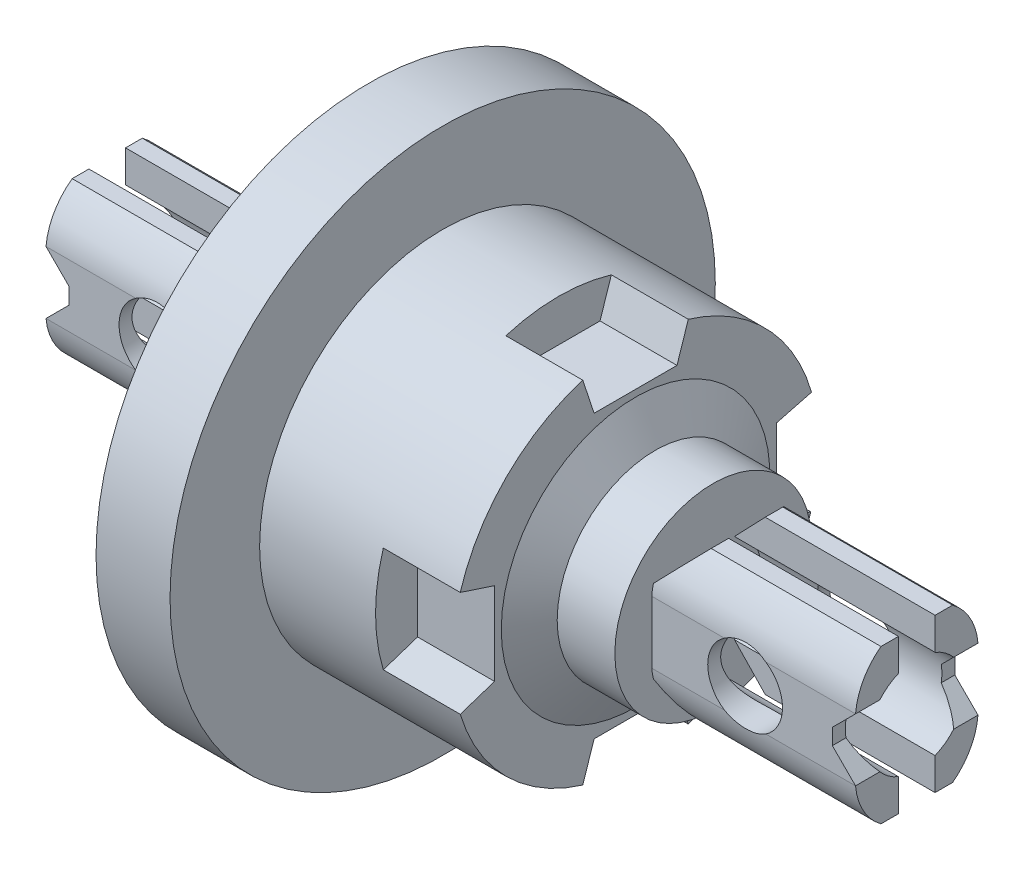
SolidWorks part; units mm, degrees
ref_plane "Front Plane" through (0, 0, 0) normal (0, 0, 1) x (1, 0, 0)
ref_plane "Top Plane" through (0, 0, 0) normal (0, 1, 0) x (1, 0, 0)
ref_plane "Right Plane" through (0, 0, 0) normal (1, 0, 0) x (0, 0, -1)
sketch "Sketch1" plane through (0, 0, 0) normal (0, 0, 1) x (1, 0, 0)
  line L0 (-42.2453, 0) -> (55.943, 0) construction
  line L1 (32.766, 0) -> (32.766, 8.001) construction
  line L2 (32.766, 8.001) -> (28.067, 8.001) construction
  line L3 (28.067, 8.001) -> (26.4541, 10.9474) construction
  line L4 (26.4541, 10.9474) -> (26.4541, 14.9225) construction
  line L5 (26.4541, 14.9225) -> (10.7315, 14.9225) construction
  line L6 (10.7315, 14.9225) -> (10.7315, 22.225) construction
  line L7 (10.7315, 22.225) -> (4.699, 22.225) construction
  line L8 (4.699, 22.225) -> (4.699, 8.001) construction
  line L9 (4.699, 8.001) -> (0, 8.001) construction
  line L10 (0, 8.001) -> (0, 0) construction
  line L11 (32.766, 0) -> (32.766, 8.001)
  line L12 (32.766, 8.001) -> (28.067, 8.001)
  line L13 (28.067, 8.001) -> (26.4541, 10.9474)
  line L14 (26.4541, 10.9474) -> (26.4541, 14.9225)
  line L15 (26.4541, 14.9225) -> (10.7315, 14.9225)
  line L16 (10.7315, 14.9225) -> (10.7315, 22.225)
  line L17 (10.7315, 22.225) -> (4.699, 22.225)
  line L18 (4.699, 22.225) -> (4.699, 8.001)
  line L19 (4.699, 8.001) -> (0, 8.001)
  line L20 (0, 8.001) -> (0, 0)
  line L21 (32.766, 0) -> (0, 0)
  dimension "D1" = 8.001
  dimension "D2" = 14.9225
  dimension "D3" = 22.225
  dimension "D4" = 4.699
  dimension "D5" = 15.7226
  dimension "D6" = 6.0325
  dimension "D7" = 4.699
  dimension "D8" = 32.766
  dimension "D9" = 2.9464
revolve "Revolve1" add sketch "Sketch1" angle 360 about L0
sketch "Sketch2" plane through (26.4541, 0, 0) normal (1, 0, 0) x (0, 0, -1)
  line L0 (0, 14.9225) -> (0, 11.4935) construction
  line L1 (-11.4935, -3.3782) -> (-11.4935, 3.3782)
  line L2 (-3.3782, -11.4935) -> (3.3782, -11.4935)
  line L3 (14.9225, 0) -> (11.4935, 0) construction
  line L4 (0, -14.9225) -> (0, -11.4935) construction
  line L5 (-14.9225, 0) -> (-11.4935, 0) construction
  line L6 (11.4935, 3.3782) -> (11.4935, -3.3782)
  line L7 (3.3782, 11.4935) -> (-3.3782, 11.4935)
  line L8 (3.3782, 11.4935) -> (4.3001, 14.2895)
  line L9 (-3.3782, 11.4935) -> (-4.3001, 14.2895)
  line L10 (-11.4935, 3.3782) -> (-14.2895, 4.3001)
  line L11 (-11.4935, -3.3782) -> (-14.2895, -4.3001)
  line L12 (3.3782, -11.4935) -> (4.3001, -14.2895)
  line L13 (-3.3782, -11.4935) -> (-4.3001, -14.2895)
  line L14 (11.4935, -3.3782) -> (14.2895, -4.3001)
  line L15 (11.4935, 3.3782) -> (14.3437, 4.1158)
  circle A0 centre (0, 0) radius 14.9225 construction
  circle A1 centre (0, 0) radius 14.9225 construction
  arc A2 (-14.2895, -4.3001) -> (-14.2895, 4.3001) centre (0, 0) cw
  arc A3 (-4.3001, -14.2895) -> (4.3001, -14.2895) centre (0, 0) ccw
  arc A4 (14.2895, -4.3001) -> (14.3437, 4.1158) centre (0, 0) ccw
  arc A5 (-4.3001, 14.2895) -> (4.3001, 14.2895) centre (0, 0) cw
  point P11 (-11.4935, 0)
  point P20 (0, -11.4935)
  point P23 (11.4935, 0)
  point P26 (0, 11.4935)
  dimension "D1" = 3.429
  dimension "D2" = 6.7564
extrude "Cut-Extrude1" cut sketch "Sketch2" against normal blind 6.2738
sketch "Sketch4" plane through (0, 0, 0) normal (0, 0, 1) x (1, 0, 0)
  line L0 (32.766, -3.3749) -> (35.5346, -6.2611)
  line L1 (32.766, -8.001) -> (32.766, 8.001) construction
  line L2 (32.766, 3.3749) -> (35.5346, 6.2611)
  line L3 (35.5346, 6.2611) -> (49.3776, 6.2611)
  line L4 (49.3776, 6.2611) -> (49.3776, 2.54)
  line L5 (49.3776, 2.54) -> (47.4877, 0.6501)
  line L6 (47.4877, 0.6501) -> (47.4877, -0.6501)
  line L7 (47.4877, -0.6501) -> (49.3776, -2.54)
  line L8 (49.3776, -2.54) -> (49.3776, -6.2611)
  line L9 (49.3776, -6.2611) -> (35.5346, -6.2611)
  line L10 (32.766, 0) -> (59.4917, 0) construction
  line L11 (0, 0) -> (-26.7257, 0) construction
  line L12 (0, 0) -> (32.766, 0) construction
  line L13 (16.383, 0) -> (16.383, 15.8061) construction
  line L14 (-16.6116, -6.2611) -> (-2.7686, -6.2611)
  line L15 (-16.6116, -2.54) -> (-16.6116, -6.2611)
  line L16 (-14.7217, -0.6501) -> (-16.6116, -2.54)
  line L17 (-14.7217, 0.6501) -> (-14.7217, -0.6501)
  line L18 (-16.6116, 2.54) -> (-14.7217, 0.6501)
  line L19 (-16.6116, 6.2611) -> (-16.6116, 2.54)
  line L20 (-2.7686, 6.2611) -> (-16.6116, 6.2611)
  line L21 (0, 3.3749) -> (-2.7686, 6.2611)
  line L22 (0, -3.3749) -> (-2.7686, -6.2611)
  line L23 (32.766, -3.3749) -> (32.766, 3.3749)
  line L24 (0, -3.3749) -> (0, 3.3749)
  circle A0 centre (40.3757, 0) radius 3.048
  circle A1 centre (-7.6097, 0) radius 3.048
  dimension "D4" = 6.096
  dimension "D1" = 12.5222
  dimension "D2" = 2.7686
  dimension "D3" = 5.08
  dimension "D5" = 7.112
  dimension "D6" = 16.6116
  dimension "D7" = 1.3001
  dimension "D8" = 3.9994
extrude "Boss-Extrude1" add sketch "Sketch4" along normal mid plane 9.9822
sketch "Sketch5" plane through (-16.6116, 0, 0) normal (-1, 0, 0) x (0, 0, 1)
  line L0 (0, 7.3348) -> (0, -10.3947) construction
  line L1 (1.4922, 3.6432) -> (1.4923, 6.2611)
  line L2 (-1.4922, 3.6432) -> (-1.4923, 6.2611)
  line L3 (4.9911, 6.2611) -> (-4.9911, 6.2611) construction
  line L4 (-1.4922, -3.6432) -> (-1.4922, -6.2611)
  line L5 (4.9911, -6.2611) -> (-4.9911, -6.2611) construction
  line L6 (1.4922, -3.6432) -> (1.4923, -6.2611)
  line L7 (-1.4923, 6.2611) -> (1.4923, 6.2611)
  line L8 (-1.4922, -6.2611) -> (1.4923, -6.2611)
  line L9 (4.9911, 2.54) -> (4.9911, 6.2611)
  line L10 (4.9911, 6.2611) -> (2.8575, 6.2611)
  line L11 (-4.9911, 2.54) -> (-4.9911, 6.2611)
  line L12 (-4.9911, 6.2611) -> (-2.8575, 6.2611)
  line L13 (-4.9911, -2.54) -> (-4.9911, -6.2611)
  line L14 (-4.9911, -6.2611) -> (-2.8575, -6.2611)
  line L15 (4.9911, -2.54) -> (4.9911, -6.2611)
  line L16 (4.9911, -6.2611) -> (2.8575, -6.2611)
  arc A0 (1.4922, -3.6432) -> (1.4922, 3.6432) centre (0, 0) ccw
  arc A1 (-1.4922, 3.6432) -> (-1.4922, -3.6432) centre (0, 0) ccw
  arc A2 (4.9911, 2.54) -> (2.8575, 6.2611) centre (-0.1725, 2.0515) ccw
  arc A3 (-4.9911, 2.54) -> (-2.8575, 6.2611) centre (0.1725, 2.0515) cw
  arc A4 (-4.9911, -2.54) -> (-2.8575, -6.2611) centre (0.1725, -2.0515) ccw
  arc A5 (4.9911, -2.54) -> (2.8575, -6.2611) centre (-0.1725, -2.0515) cw
  dimension "D1" = 7.874
  dimension "D3" = 5.1867
  dimension "D2" = 2.9845
  dimension "D4" = 2.1336
extrude "Cut-Extrude2" cut sketch "Sketch5" against normal up to surface (16.6116 mm away) up to face at (0, 0, 8.001)
sketch "Sketch6" plane through (49.3776, 0, 0) normal (1, 0, 0) x (0, 0, -1)
  line L0 (0, 6.2611) -> (0, -6.2611) construction
  line L1 (-4.9911, 6.2611) -> (4.9911, 6.2611) construction
  line L2 (-4.9911, -6.2611) -> (4.9911, -6.2611) construction
  line L3 (1.4922, 3.6432) -> (1.4922, 6.2611)
  line L4 (-1.4922, 3.6432) -> (-1.4922, 6.2611)
  line L5 (-1.4922, -3.6432) -> (-1.4922, -6.2611)
  line L6 (1.4923, -3.6432) -> (1.4923, -6.2611)
  line L7 (-1.4922, 6.2611) -> (1.4922, 6.2611)
  line L8 (-1.4922, -6.2611) -> (1.4923, -6.2611)
  line L9 (-4.9911, -2.54) -> (-4.9911, -6.2611)
  line L10 (2.9191, -6.2611) -> (4.9911, -6.2611)
  line L11 (-4.9911, 2.54) -> (-4.9911, 6.2611) construction
  line L13 (4.9911, 6.2611) -> (2.9191, 6.2611)
  line L14 (-2.9191, 6.2611) -> (-4.9911, 6.2611)
  line L15 (-4.9911, -2.54) -> (4.9911, -2.54) construction
  line L16 (4.9911, -6.2611) -> (4.9911, -2.54) construction
  line L17 (4.9911, 2.54) -> (4.9911, 6.2611)
  line L18 (-4.9911, -6.2611) -> (-2.9191, -6.2611)
  line L19 (4.9911, -6.2611) -> (4.9911, -2.54)
  line L20 (-4.9911, 6.2611) -> (-4.9911, 2.54)
  arc A0 (1.4923, -3.6432) -> (1.4922, 3.6432) centre (0, 0) ccw
  arc A1 (-1.4922, 3.6432) -> (-1.4922, -3.6432) centre (0, 0) ccw
  arc A2 (-4.9911, -2.54) -> (-2.9191, -6.2611) centre (0.1773, -2.0995) ccw
  arc A3 (-2.9191, 6.2611) -> (-4.9911, 2.54) centre (0.1773, 2.0995) ccw
  arc A5 (4.9911, 2.54) -> (2.9191, 6.2611) centre (-0.1773, 2.0995) ccw
  arc A6 (4.9911, -2.54) -> (2.9191, -6.2611) centre (-0.1773, -2.0995) cw
  dimension "D1" = 7.874
  dimension "D3" = 5.1872
  dimension "D2" = 2.9845
  dimension "D4" = 2.072
extrude "Cut-Extrude5" cut sketch "Sketch6" against normal up to surface (16.6116 mm away)
